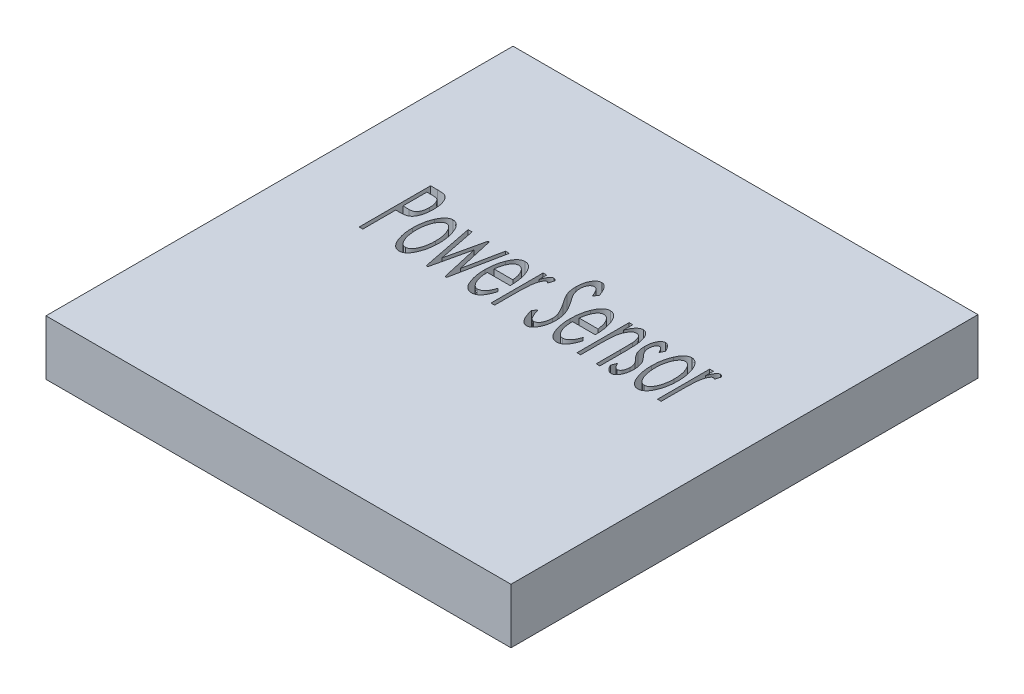
SolidWorks part; units mm, degrees
ref_plane "Front Plane" through (0, 0, 0) normal (0, 0, 1) x (1, 0, 0)
ref_plane "Top Plane" through (0, 0, 0) normal (0, 1, 0) x (1, 0, 0)
ref_plane "Right Plane" through (0, 0, 0) normal (1, 0, 0) x (0, 0, -1)
sketch "Sketch1" plane through (0, 0, 0) normal (0, 1, 0) x (1, 0, 0)
  line L1 (-22.8, 22.9) -> (0, 22.9)
  line L2 (-22.8, 22.9) -> (-22.8, 0)
  line L3 (-22.8, 0) -> (0, 0)
  line L4 (0, 22.9) -> (0, 0)
  dimension "D1" = 22.9
  dimension "D2" = 22.8
extrude "Boss-Extrude1" add sketch "Sketch1" along normal blind 2.7
sketch "Sketch2" plane through (0, 2.7, 0) normal (0, 1, 0) x (1, 0, 0)
  line L0 (-22.8, 11.45) -> (0, 11.45) construction
  line L1 (-22.8, 22.9) -> (-22.8, 0) construction
  line L2 (0, 0) -> (0, 22.9) construction
  text T0 "Power Sensor" font "Century Gothic" height 3.5
extrude "Cut-Extrude1" cut sketch "Sketch2" against normal blind 1
